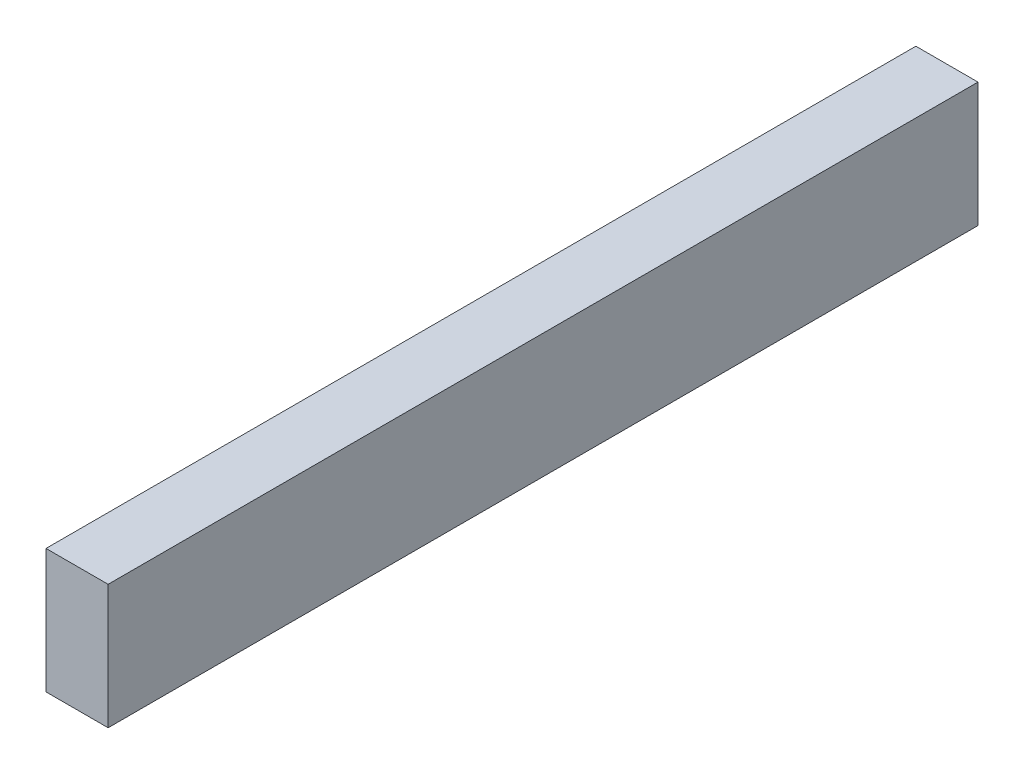
SolidWorks part; units mm, degrees
ref_plane "Front Plane" through (0, 0, 0) normal (0, 0, 1) x (1, 0, 0)
ref_plane "Top Plane" through (0, 0, 0) normal (0, 1, 0) x (1, 0, 0)
ref_plane "Right Plane" through (0, 0, 0) normal (1, 0, 0) x (0, 0, -1)
sketch "Sketch1" plane through (0, 0, 0) normal (0, 0, 1) x (1, 0, 0)
  line L1 (-25.4, -50.8) -> (25.4, -50.8)
  line L2 (-25.4, -50.8) -> (-25.4, 50.8)
  line L3 (-25.4, 50.8) -> (25.4, 50.8)
  line L4 (25.4, -50.8) -> (25.4, 50.8)
  line L5 (-25.4, -50.8) -> (25.4, 50.8) construction
  line L6 (-25.4, 50.8) -> (25.4, -50.8) construction
  point P0 (0, 0)
  dimension "D1" = 50.8
  dimension "D2" = 101.6
extrude "Boss-Extrude1" add sketch "Sketch1" along normal blind 711.2
